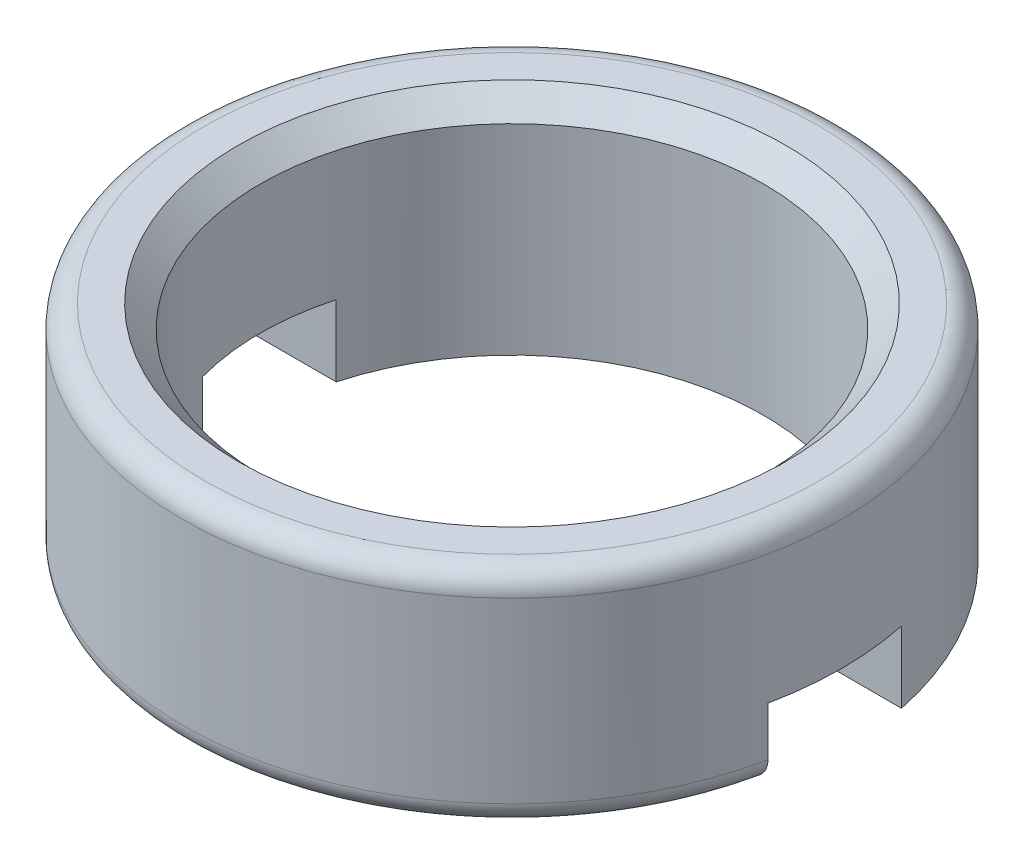
SolidWorks part; units mm, degrees
ref_plane "Front Plane" through (0, 0, 0) normal (0, 0, 1) x (1, 0, 0)
ref_plane "Top Plane" through (0, 0, 0) normal (0, 1, 0) x (1, 0, 0)
ref_plane "Right Plane" through (0, 0, 0) normal (1, 0, 0) x (0, 0, -1)
sketch "Sketch1" plane through (0, 0, 0) normal (0, 1, 0) x (1, 0, 0)
  circle A0 centre (0, 0) radius 7.4
  circle A1 centre (0, 0) radius 5.65
  dimension "D1" = 14.8
  dimension "D2" = 11.3
extrude "Boss-Extrude1" add sketch "Sketch1" along normal blind 5
sketch "Sketch2" plane through (0, 0, 0) normal (0, 1, 0) x (1, 0, 0)
  line L1 (-13.7487, 1.5) -> (13.7487, 1.5)
  line L2 (-13.7487, 1.5) -> (-13.7487, -1.5)
  line L3 (-13.7487, -1.5) -> (13.7487, -1.5)
  line L4 (13.7487, 1.5) -> (13.7487, -1.5)
  line L5 (-13.7487, 1.5) -> (13.7487, -1.5) construction
  line L6 (-13.7487, -1.5) -> (13.7487, 1.5) construction
  point P0 (0, 0)
  dimension "D1" = 3
extrude "Cut-Extrude2" cut sketch "Sketch2" along normal blind 1.6
fillet "Fillet1" radius 0.5 3 edges at (0, 0, 5.65) (0, 5, 7.4) (0, 0, 7.4)
chamfer "Chamfer1" distance 0.5 angle 45 1 edges at (0, 5, 5.65)
